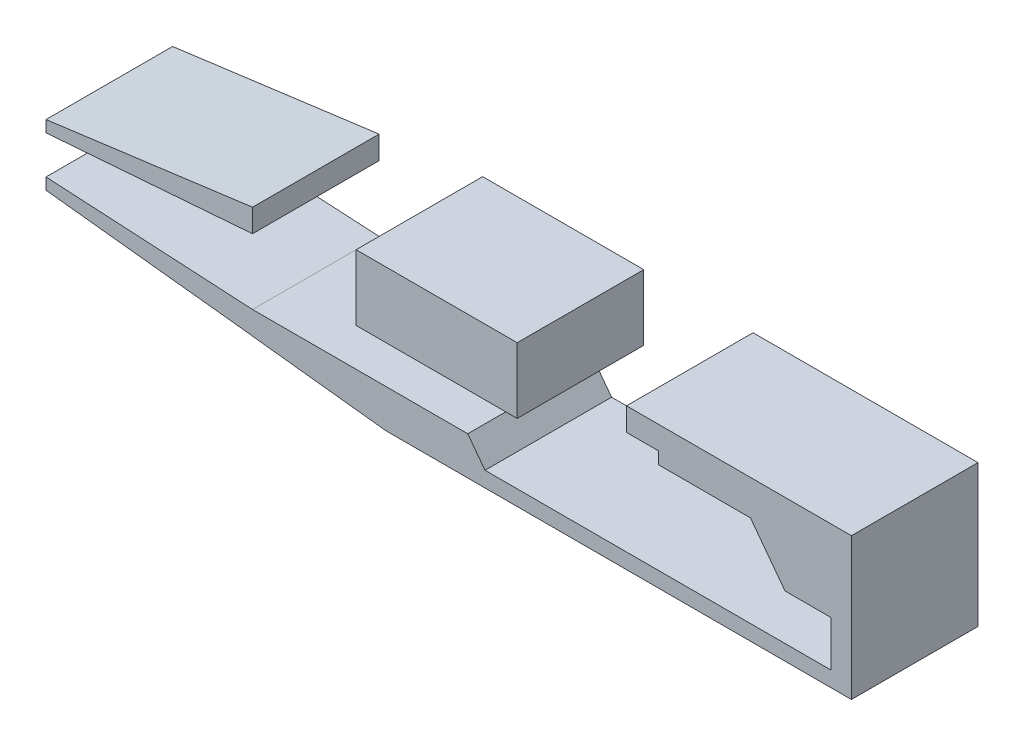
SolidWorks part; units mm, degrees
ref_plane "Front Plane" through (0, 0, 0) normal (0, 0, 1) x (1, 0, 0)
ref_plane "Top Plane" through (0, 0, 0) normal (0, 1, 0) x (1, 0, 0)
ref_plane "Right Plane" through (0, 0, 0) normal (1, 0, 0) x (0, 0, -1)
sketch "Sketch1" plane through (0, 0, 0) normal (0, 1, 0) x (1, 0, 0)
  line L1 (-350, 55) -> (350, 55)
  line L2 (-350, 55) -> (-350, -55)
  line L3 (-350, -55) -> (350, -55)
  line L4 (350, 55) -> (350, -55)
  line L5 (0, -55) -> (0, 55) construction
  line L6 (-55, 0) -> (55, 0) construction
  dimension "D1" = 350
  dimension "D2" = 110
  dimension "D3" = 55
extrude "Boss-Extrude1" add sketch "Sketch1" along normal blind 110
sketch "Sketch3" plane through (0, 0, 55) normal (0, 0, 1) x (1, 0, 0)
  line L0 (59.5, 110) -> (59.5, 53) construction
  line L1 (-350, 110) -> (350, 110) construction
  line L2 (59.5, 53) -> (-80.5, 53) construction
  line L3 (-80.5, 53) -> (-80.5, 110) construction
  line L4 (350, 110) -> (350, 0) construction
  line L5 (-350, 0) -> (350, 0) construction
  line L6 (-80.5, 110) -> (-170.5, 110) construction
  line L7 (-170.5, 0) -> (-170.5, 20) construction
  line L8 (-80.5, 0) -> (-80.5, 20) construction
  line L9 (-80.5, 20) -> (16.5443, 20) construction
  line L10 (-350, 20) -> (-350, 30) construction
  line L11 (-350, 110) -> (-350, 0) construction
  line L12 (-350, 30) -> (-350, 63.2185) construction
  line L13 (182.25, 79.5417) -> (262.25, 79.5417)
  line L14 (-170.5, 20) -> (-80.5, 20)
  line L15 (16.5443, 20) -> (31.5443, 0) construction
  line L16 (-170.5, 20) -> (-170.5, 77) construction
  line L17 (-170.5, 77) -> (-170.5, 97) construction
  line L18 (-350, 63.2185) -> (-350, 73.2185) construction
  line L19 (-80.5, 20) -> (16.5443, 20)
  line L20 (350, 110) -> (210, 110) construction
  line L21 (210, 110) -> (350, 110)
  line L22 (59.5, 110) -> (154.5, 110) construction
  line L23 (350, 110) -> (350, 0)
  line L24 (210, 110) -> (154.5, 110)
  line L25 (154.5, 110) -> (154.5, 90)
  line L26 (154.5, 90) -> (182.25, 90)
  line L27 (182.25, 90) -> (182.25, 79.5417)
  line L28 (292.25, 39.5417) -> (402.25, 39.5417) construction
  line L31 (-350, 30) -> (-170.5, 20)
  line L32 (16.5443, 20) -> (31.5443, 0)
  line L33 (31.5443, 0) -> (182.25, 0)
  line L34 (59.5, 110) -> (59.5, 53)
  line L35 (59.5, 53) -> (-80.5, 53)
  line L36 (-80.5, 53) -> (-80.5, 110)
  line L37 (182.25, 0) -> (31.5443, 0)
  line L38 (-170.5, 97) -> (-350, 73.2185)
  line L39 (-350, 73.2185) -> (-350, 63.2185)
  line L40 (-350, 63.2185) -> (-170.5, 77)
  line L41 (-170.5, 77) -> (-170.5, 97)
  line L42 (59.5, 110) -> (-80.5, 110)
  line L43 (-350, 30) -> (-350, 20) construction
  line L44 (55, 0) -> (-55, 0) construction
  line L45 (182.25, 0) -> (262.25, 0)
  line L46 (-170.5, 0) -> (-350, 20)
  line L48 (262.25, 79.5417) -> (292.25, 39.5417)
  line L49 (292.25, 39.5417) -> (332.25, 39.5417)
  line L50 (332.25, 39.5417) -> (332.25, 0)
  line L51 (332.25, 0) -> (262.25, 0)
  line M8 (-350, 0) -> (350, 0)
  line M10 (350, 110) -> (-350, 110)
  line M11 (-350, 110) -> (-350, 0)
  dimension "D1" = 290.5
  dimension "D2" = 53
  dimension "D3" = 140
  dimension "D4" = 90
  dimension "D5" = 80
  dimension "D6" = 150
  dimension "D8" = 10
extrude "Cut-Extrude1" cut sketch "Sketch3" against normal blind 120 contours L41 L40 L31 L14 L19 L32 L27 L26 L25 L34 L35 L36 L38 M11 M8 M10 | L46 M8 M11
sketch "Sketch5" plane through (0, 0, 0) normal (0, 0, 1) x (1, 0, 0)
  line L0 (-171.4964, 0) -> (-54.7522, -13.3179)
  line L1 (-171.4964, 0) -> (350, 0)
  line L3 (-54.7522, -13.3179) -> (350, -13.3179)
  line L4 (350, 0) -> (350, -13.3179)
extrude "Boss-Extrude9" add sketch "Sketch5" along normal mid plane 110
